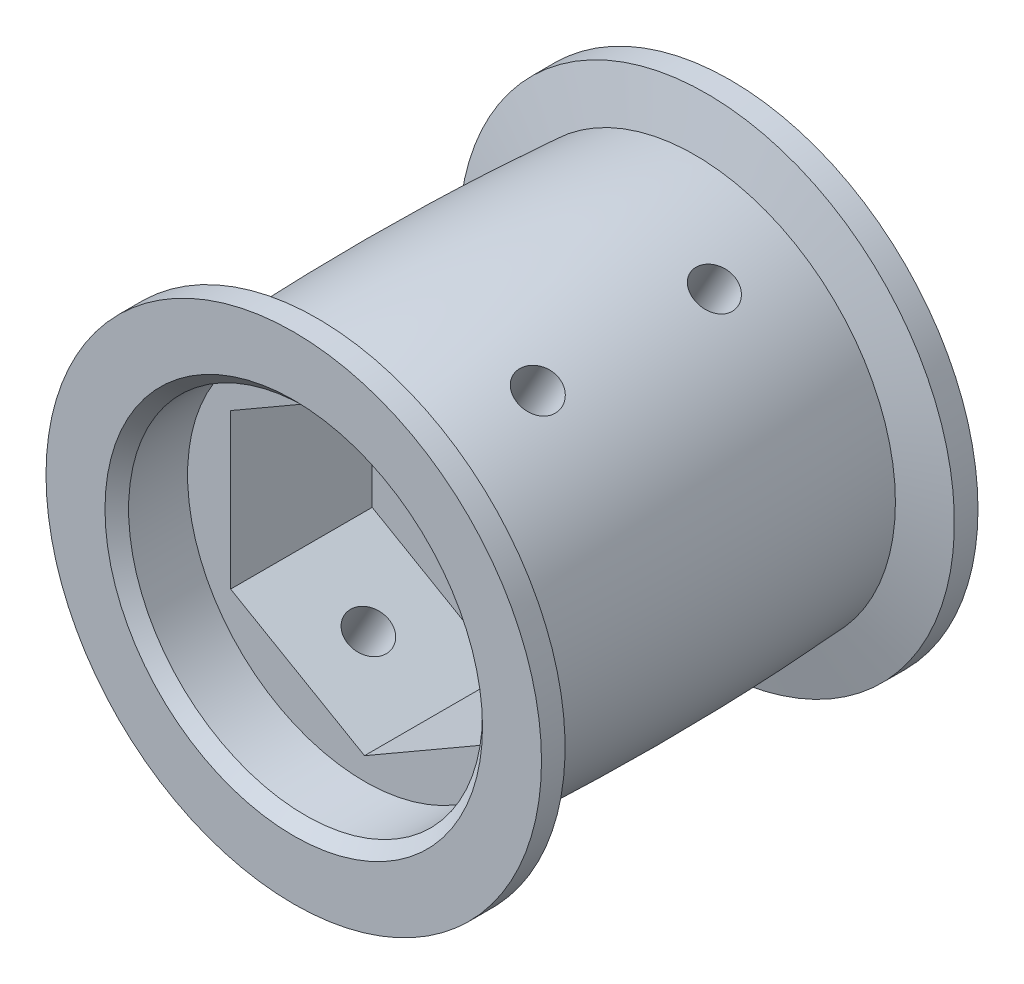
SolidWorks part; units mm, degrees
ref_plane "Plan de face" through (0, 0, 0) normal (0, 0, 1) x (1, 0, 0)
ref_plane "Plan de dessus" through (0, 0, 0) normal (0, 1, 0) x (1, 0, 0)
ref_plane "Plan de droite" through (0, 0, 0) normal (1, 0, 0) x (0, 0, -1)
sketch "Esquisse1" plane through (0, 0, 0) normal (0, 0, 1) x (1, 0, 0)
  circle A0 centre (0, 0) radius 3.25
  circle A1 centre (0, 0) radius 21
  dimension "D1" = 42
  dimension "D2" = 6.5
extrude "Boss.-Extru.1" add sketch "Esquisse1" along normal blind 31
sketch "Esquisse2" plane through (0, 0, 31) normal (0, 0, 1) x (1, 0, 0)
  circle A0 centre (0, 0) radius 21
  circle A1 centre (0, 0) radius 15
  circle A2 centre (0, 0) radius 21 construction
  dimension "D1" = 30
extrude "Boss.-Extru.2" add sketch "Esquisse2" along normal blind 6
sketch "Esquisse9" plane through (0, 0, 31) normal (0, 0, 1) x (1, 0, 0)
  line L0 (0, 0) -> (0, 26.2117) construction
  line L1 (11.35, -6.5529) -> (11.35, 6.5529)
  line L2 (11.35, 6.5529) -> (0, 13.1059)
  line L3 (0, 13.1059) -> (-11.35, 6.5529)
  line L4 (-11.35, 6.5529) -> (-11.35, -6.5529)
  line L5 (-11.35, -6.5529) -> (0, -13.1059)
  line L6 (0, -13.1059) -> (11.35, -6.5529)
  circle A0 centre (0, 0) radius 11.35 construction
  dimension "D1" = 22.7
extrude "Enlèv. mat.-Extru.9" cut sketch "Esquisse9" against normal offset from surface (12 mm away) 19 up to face at (21, 0, 0)
chamfer "Chanfrein1" distance 1 angle 45 1 edges at (15, 0, 37)
sketch "Esquisse10" plane through (0, 0, 0) normal (1, 0, 0) x (0, 0, -1)
  line L0 (-35, 21) -> (-2, 21)
  line L1 (0, 21) -> (-37, 21) construction
  line L2 (-2, 21) -> (-3, 17)
  line L3 (-3, 17) -> (-34, 17) construction
  line L4 (-34, 17) -> (-35, 21)
  line L5 (-19.6787, 17.5) -> (-7.7815, 17.5) construction
  line L6 (0, 0) -> (-50.6564, 0) construction
  arc A0 (-34, 17) -> (-3, 17) centre (-18.5, -223) cw
  dimension "D6" = 0.5
  dimension "D1" = 4
  dimension "D2" = 2
  dimension "D3" = 2
  dimension "D4" = 1
  dimension "D5" = 1
revolve "Enlèvement de matière-Révolution1" cut sketch "Esquisse10" angle 360 about L6
sketch "Esquisse11" plane through (0, 0, 0) normal (0, 0, -1) x (-1, 0, 0)
  line L0 (0, 0) -> (18.1865, 10.5) construction
  line L1 (0, 0) -> (-18.1865, 10.5) construction
  line L2 (0, 0) -> (0, -21) construction
  circle A0 centre (0, 0) radius 21 construction
  circle A1 centre (-6.9282, 4) radius 1.25
  circle A2 centre (6.9282, 4) radius 1.25
  circle A3 centre (0, -8) radius 1.25
  circle A4 centre (0, 0) radius 8 construction
  dimension "D3" = 2.5
  dimension "D4" = 16
  dimension "D1" = 120
  dimension "D2" = 120
extrude "Enlèv. mat.-Extru.10" cut sketch "Esquisse11" against normal through all
sketch "Esquisse12" plane through (0, 0, 0) normal (0, 0, -1) x (-1, 0, 0)
  circle A0 centre (-6.9282, 4) radius 4.25
  circle A1 centre (6.9282, 4) radius 4.25
  circle A2 centre (0, -8) radius 4.25
  dimension "D1" = 8.5
extrude "Enlèv. mat.-Extru.11" cut sketch "Esquisse12" against normal blind 4
sketch "Esquisse13" plane through (-5.675, -9.8294, 0) normal (0.5, 0.866, 0) x (0.866, -0.5, 0)
  line L0 (-6.5529, -25) -> (6.5529, -25) construction
  line L1 (-6.5529, -19) -> (-6.5529, -31) construction
  line L2 (6.5529, -19) -> (6.5529, -31) construction
  line L3 (0, -25) -> (0, 47.1738) construction
  circle A0 centre (0, -25) radius 1.75
  circle A1 centre (0, -10) radius 1.75
  dimension "D1" = 3.5
  dimension "D2" = 15
extrude "Enlèv. mat.-Extru.12" cut sketch "Esquisse13" against normal through all and the other way through all
